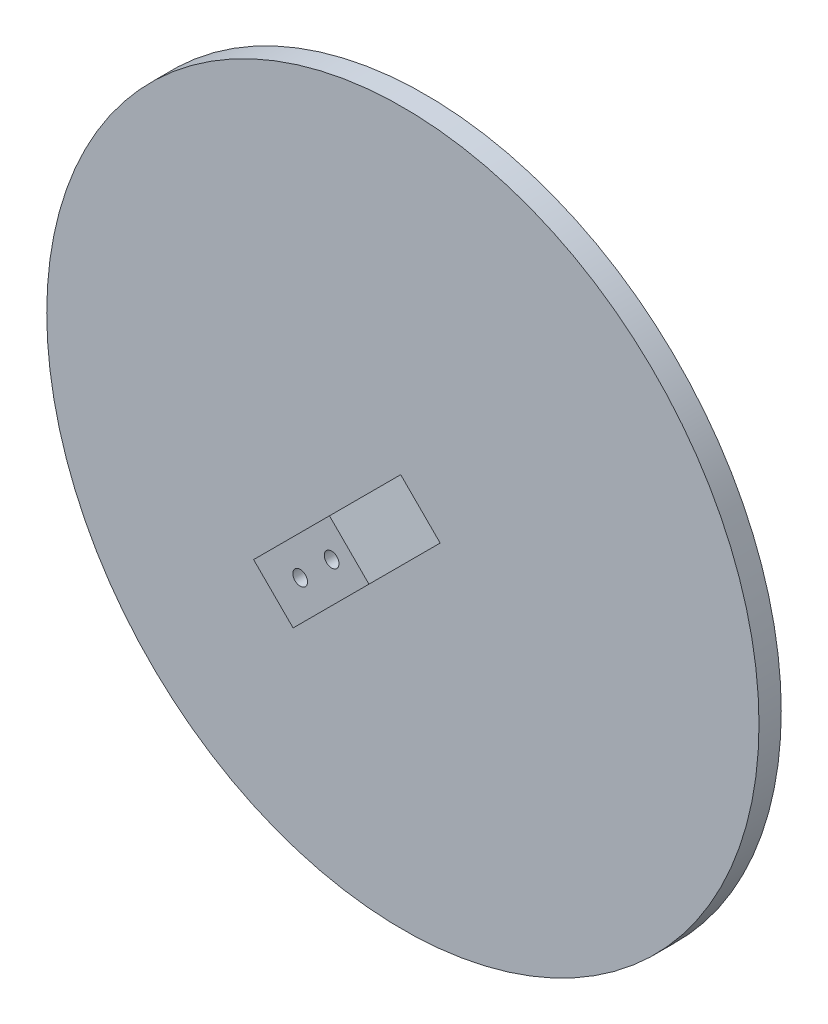
SolidWorks part; units mm, degrees
ref_plane "Front Plane" through (0, 0, 0) normal (0, 0, 1) x (1, 0, 0)
ref_plane "Top Plane" through (0, 0, 0) normal (0, 1, 0) x (1, 0, 0)
ref_plane "Right Plane" through (0, 0, 0) normal (1, 0, 0) x (0, 0, -1)
ref_plane "Plane2" through (0, 0, -22.7) normal (0, 0, -1) x (-1, 0, 0)
sketch "Sketch2" plane through (0, 0, -22.7) normal (0, 0, -1) x (-1, 0, 0)
  line L0 (-119.6181, 49.8516) -> (-102.5819, 32.8154)
  line L1 (-119.6181, 49.8516) -> (-110.751, 58.7188)
  line L2 (-102.5819, 32.8154) -> (-93.7148, 41.6826)
  line L3 (-110.751, 58.7188) -> (-93.7148, 41.6826)
  line L4 (-119.6181, 49.8516) -> (-66.5851, -3.1814) construction
  line L5 (-66.5851, -3.1814) -> (-119.6181, 49.8516) construction
  dimension "D1" = 24.0928
  dimension "D2" = 12.5401
extrude "Boss-Extrude1" add sketch "Sketch2" along normal blind 16
sketch "Sketch3" plane through (0, 0, -22.7) normal (0, 0, -1) x (-1, 0, 0)
  circle A0 centre (-111.2389, 50.4527) radius 1.65
  circle A1 centre (-104.1679, 43.3816) radius 1.65
  dimension "D1" = 3.3
  dimension "D2" = 3.3
extrude "Cut-Extrude1" cut sketch "Sketch3" along normal blind 27
ref_plane "Plane4" through (0, 0, -38.7) normal (0, 0, -1) x (-1, 0, 0)
sketch "Sketch4" plane through (0, 0, -38.7) normal (0, 0, -1) x (-1, 0, 0)
  circle A0 centre (-111.2389, 50.4527) radius 80
  dimension "D1" = 160
extrude "Boss-Extrude2" add sketch "Sketch4" along normal blind 5
sketch "Sketch5" plane through (0, 0, -38.7) normal (0, 0, -1) x (-1, 0, 0)
  circle A0 centre (-111.2389, 50.4527) radius 1.65
  circle A1 centre (-104.1679, 43.3816) radius 1.65
  dimension "D1" = 3.3
  dimension "D2" = 3.3
extrude "Cut-Extrude3" cut sketch "Sketch5" along normal blind 5
